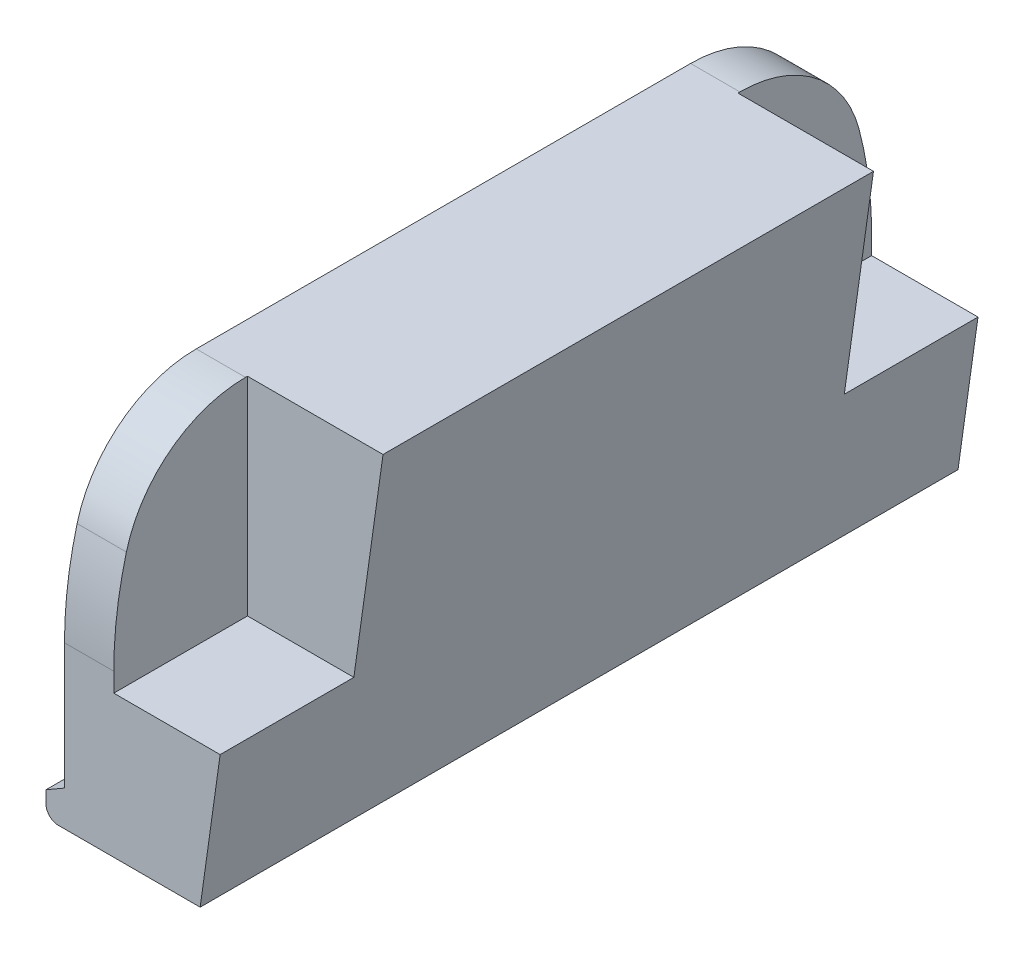
SolidWorks part; units mm, degrees
ref_plane "Front Plane" through (0, 0, 0) normal (0, 0, 1) x (1, 0, 0)
ref_plane "Top Plane" through (0, 0, 0) normal (0, 1, 0) x (1, 0, 0)
ref_plane "Right Plane" through (0, 0, 0) normal (1, 0, 0) x (0, 0, -1)
sketch "Sketch1" plane through (0, 0, 0) normal (0, 0, 1) x (1, 0, 0)
  line L0 (0, 0) -> (0.3, 0.1732)
  line L1 (0.3, 6.1075) -> (0.3, 1.7816)
  line L2 (0.3, 6.1075) -> (3.3, 6.1075)
  line L3 (3.3, 6.1075) -> (3.3, 0.6468)
  line L4 (0.3, 1.7816) -> (0.3, 0.1732)
  line L5 (0.3, 0.9774) -> (0.15, 0.0866) construction
  line L6 (2.3013, 0.5964) -> (0.3, 0.1732) construction
  line L7 (1.3155, -0.3379) -> (0.3, 0.1732) construction
  line L8 (1.3155, -0.3379) -> (3.3, 0.6468) construction
  line L9 (3.3, 0.6468) -> (3.3, -0.4)
  line L10 (3.3, -0.4) -> (0.2, -0.4)
  line L11 (0, 0) -> (0, -0.2)
  arc A0 (3.3, 0.6468) -> (2.3013, 0.5964) centre (8.5649, -113.5554) ccw construction
  arc A1 (0.2, -0.4) -> (0, -0.2) centre (0.2, -0.2) cw
  point P9 (0.3, 1.7816)
  point P10 (0, -3.0581)
  point P17 (0, -0.4)
  dimension "D1" = 0.3464
  dimension "D2" = 114.3235
  dimension "D3" = 5.9342
  dimension "D6" = 1
  dimension "D12" = 0.2
  dimension "D4" = 3
  dimension "D5" = 5.4606
  dimension "D7" = 1.6084
  dimension "D8" = 0.9033
  dimension "D9" = 1.1369
  dimension "D10" = 2.2154
  dimension "D11" = 0.4
extrude "Boss-Extrude1" add sketch "Sketch1" along normal blind 12.3
sketch "Sketch2" plane through (0, 6.1075, 0) normal (0, 1, 0) x (1, 0, 0)
  line L0 (3.3, -6.15) -> (0.3, -6.15) construction
  line L1 (3.3, 0) -> (1.1, 0)
  line L2 (3.3, 0) -> (3.3, -2.17)
  line L3 (3.3, -2.17) -> (1.1, -2.17)
  line L4 (1.1, 0) -> (1.1, -2.17)
  line L5 (3.3, -12.3) -> (3.3, 0) construction
  line L6 (0.3, -12.3) -> (0.3, 0) construction
  line L7 (3.3, -10.13) -> (1.1, -10.13)
  line L8 (3.3, -12.3) -> (3.3, -10.13)
  line L9 (3.3, -12.3) -> (1.1, -12.3)
  line L10 (1.1, -12.3) -> (1.1, -10.13)
  dimension "D1" = 2.17
  dimension "D2" = 2.2
extrude "Cut-Extrude1" cut sketch "Sketch2" against normal blind 4.2
sketch "Sketch4" plane through (0.3, 0, 0) normal (-1, 0, 0) x (0, 0, 1)
  line L0 (12.3, 0.1732) -> (12.3, 2.2159) construction
  line L1 (12.3, 6.1075) -> (12.3, 0.1732) construction
  line L2 (1.8884, 6.1075) -> (10.4116, 6.1075) construction
  line L3 (12.3, 6.1075) -> (0, 6.1075) construction
  line L4 (6.15, 6.1075) -> (6.15, 0.1732) construction
  line L5 (12.3, 0.1732) -> (0, 0.1732) construction
  line L6 (11.2391, 5.669) -> (10.4116, 6.1075) construction
  line L7 (10.4116, 6.1075) -> (12.3, 6.1075)
  line L8 (12.3, 6.1075) -> (12.3, 2.2159)
  line L9 (1.8884, 6.1075) -> (0, 6.1075)
  line L10 (0, 6.1075) -> (0, 2.2159)
  arc A0 (12.3, 2.2159) -> (11.2391, 5.669) centre (6.1496, 2.2159) ccw
  arc A1 (11.2391, 5.669) -> (10.4116, 6.1075) centre (10.4119, 5.1078) ccw
  arc A2 (1.0609, 5.669) -> (1.8884, 6.1075) centre (1.8881, 5.1078) cw
  arc A3 (0, 2.2159) -> (1.0609, 5.669) centre (6.1504, 2.2159) cw
  dimension "D1" = 8.5232
  dimension "D2" = 0.9365
  dimension "D3" = 3.6124
  dimension "D4" = 3.6665
extrude "Cut-Extrude3" cut sketch "Sketch4" against normal up to surface (0.8 mm away) up to face at (1.1, 4.0075, 11.215)
sketch "Sketch5" plane through (0.3, 0, 0) normal (-1, 0, 0) x (0, 0, 1)
  line L0 (6.15, 1.7816) -> (6.15, 0.1732) construction
  line L1 (4.65, 2.7816) -> (7.65, 2.7816)
  line L2 (4.65, 2.7816) -> (4.65, 1.7816)
  line L3 (4.65, 1.7816) -> (7.65, 1.7816)
  line L4 (7.65, 2.7816) -> (7.65, 1.7816)
  line L5 (12.3, 0.1732) -> (0, 0.1732) construction
  dimension "D1" = 1.6084
  dimension "D2" = 3
  dimension "D3" = 1
extrude "Boss-Extrude2" add sketch "Sketch5" along normal blind 0.55
sketch "Sketch6" plane through (0, 0, 7.65) normal (0, 0, 1) x (1, 0, 0)
  line L0 (0.3, 2.7816) -> (0.3, 4.3732)
  line L1 (0.3, 5.669) -> (0.3, 2.2159) construction
  line L2 (0.3, 4.3732) -> (-0.25, 2.7816)
  line L3 (-0.25, 2.7816) -> (0.3, 2.7816)
  dimension "D1" = 1.5916
extrude "Boss-Extrude3" add sketch "Sketch6" against normal up to surface (3 mm away) up to face at (0.025, 2.2816, 4.65)
sketch "Sketch7" plane through (0.3, 0, 0) normal (-1, 0, 0) x (0, 0, 1)
  line L1 (-0.5522, 6.1075) -> (12.4609, 6.1075)
  line L2 (-0.5522, 6.1075) -> (-0.5522, 5.2775)
  line L3 (-0.5522, 5.2775) -> (12.4609, 5.2775)
  line L4 (12.4609, 6.1075) -> (12.4609, 5.2775)
  line L5 (10.4119, 6.1075) -> (1.8881, 6.1075) construction
  dimension "D1" = 0.83
  dimension "D2" = 0
extrude "Cut-Extrude4" cut sketch "Sketch7" against normal through all
fillet "Fillet1" radius 2 2 edges at (0.7, 5.2775, 11.4839) (0.7, 5.2775, 0.8161)
sketch "Sketch8" plane through (0, 0, 12.3) normal (0, 0, 1) x (1, 0, 0)
  line L0 (3.3, -0.4) -> (2.5021, -0.4)
  line L1 (0.2, -0.4) -> (3.3, -0.4) construction
  line L2 (2.5021, -0.4) -> (3.3, 5.2775)
  line L3 (3.3, 5.2775) -> (3.3, -0.4)
  dimension "D1" = 8
extrude "Cut-Extrude5" cut sketch "Sketch8" against normal through all
